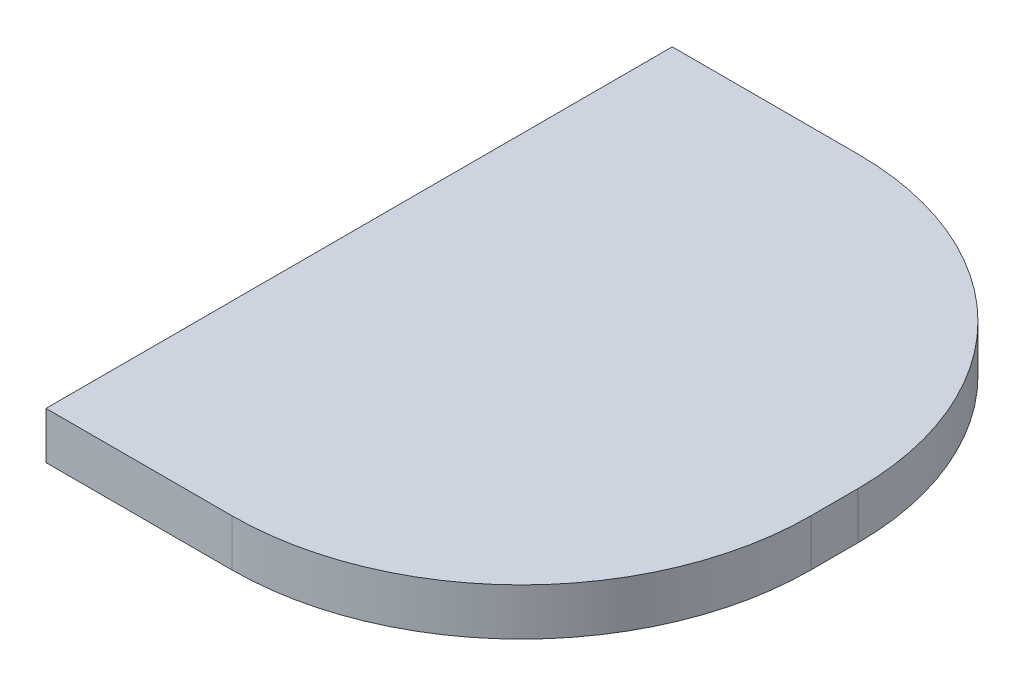
SolidWorks part; units mm, degrees
ref_plane "Front Plane" through (0, 0, 0) normal (0, 0, 1) x (1, 0, 0)
ref_plane "Top Plane" through (0, 0, 0) normal (0, 1, 0) x (1, 0, 0)
ref_plane "Right Plane" through (0, 0, 0) normal (1, 0, 0) x (0, 0, -1)
sketch "Sketch1" plane through (0, 0, 0) normal (0, 0, 1) x (1, 0, 0)
  line L1 (-15.1833, -1.5) -> (15.1833, -1.5)
  line L2 (-15.1833, -1.5) -> (-15.1833, 1.5)
  line L3 (-15.1833, 1.5) -> (15.1833, 1.5)
  line L4 (15.1833, -1.5) -> (15.1833, 1.5)
  line L5 (-15.1833, -1.5) -> (15.1833, 1.5) construction
  line L6 (-15.1833, 1.5) -> (15.1833, -1.5) construction
  point P0 (0, 0)
  dimension "D1" = 3
extrude "Boss-Extrude1" add sketch "Sketch1" along normal blind 40
fillet "Fillet1" radius 18.5 2 edges at (15.1833, 0, 0) (15.1833, 0, 40)
